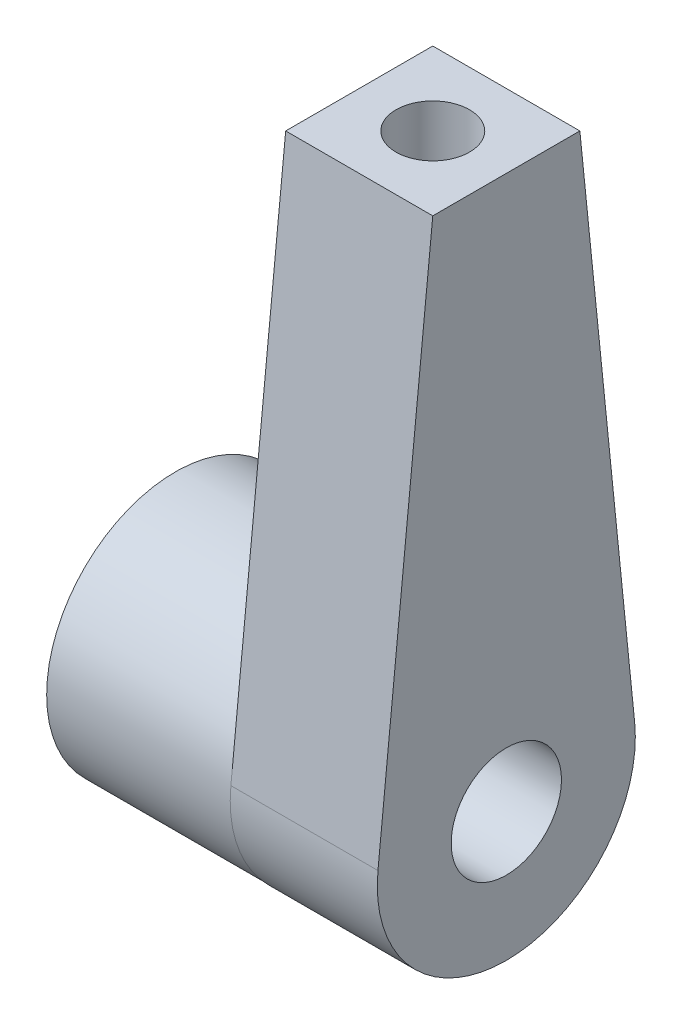
SolidWorks part; units mm, degrees
ref_plane "Front Plane" through (0, 0, 0) normal (0, 0, 1) x (1, 0, 0)
ref_plane "Top Plane" through (0, 0, 0) normal (0, 1, 0) x (1, 0, 0)
ref_plane "Right Plane" through (0, 0, 0) normal (1, 0, 0) x (0, 0, -1)
sketch "Sketch1" plane through (0, 0, 0) normal (1, 0, 0) x (0, 0, -1)
  line L0 (-4, 0) -> (-6.9812, -29.349)
  line L1 (0, -291.1569) -> (0, 14266.6882) construction
  line L2 (-4, 0) -> (4, 0)
  line L3 (4, 0) -> (6.9812, -29.349)
  arc A0 (-6.9812, -29.349) -> (6.9812, -29.349) centre (0, -30.0581) ccw
  circle A1 centre (0, -30.0581) radius 3
  dimension "D7" = 6
  dimension "D1" = 29.5
  dimension "D2" = 29.5
  dimension "D3" = 8
  dimension "D4" = 4
  dimension "D5" = 95.8
  dimension "D6" = 95.8
extrude "Boss-Extrude1" add sketch "Sketch1" against normal blind 8 contours L0 A0 L3 L2 | A1
sketch "Sketch2" plane through (-8, 0, 0) normal (-1, 0, 0) x (0, 0, 1)
  circle A0 centre (0, -30.0581) radius 7
  circle A1 centre (0, -30.0581) radius 3 construction
  circle A2 centre (0, -30.0581) radius 3
  dimension "D1" = 14
extrude "Boss-Extrude2" add sketch "Sketch2" along normal blind 10 contours A0
sketch "Sketch3" plane through (0, 0, 0) normal (0, 1, 0) x (1, 0, 0)
  line L0 (0, -4) -> (0, 4) construction
  line L1 (-8, 4) -> (0, 4) construction
  circle A0 centre (-4, 0) radius 2
  dimension "D1" = 4
  dimension "D2" = 4
  dimension "D3" = 4
extrude "Cut-Extrude1" cut sketch "Sketch3" against normal blind 22 contours A0
